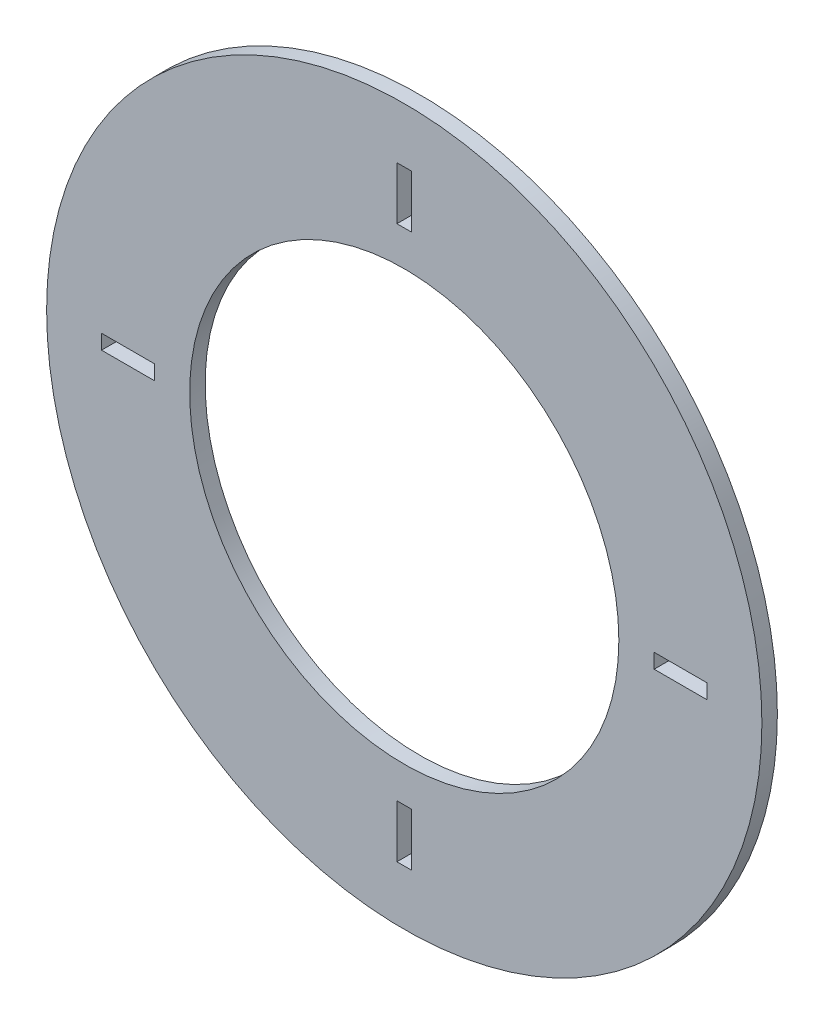
SolidWorks part; units mm, degrees
ref_plane "Front Plane" through (0, 0, 0) normal (1, 0, 0) x (0, 1, 0)
ref_plane "Top Plane" through (0, 0, 0) normal (0, 0, 1) x (0, 1, 0)
ref_plane "Right Plane" through (0, 0, 0) normal (0, 1, 0) x (-1, 0, 0)
sketch "Sketch1" plane through (0, 0, 0) normal (0, 0, 1) x (0, 1, 0)
  circle A0 centre (0, 0) radius 63.5
  circle A1 centre (0, 0) radius 38.1
  dimension "D1" = 127
  dimension "D2" = 25.4
extrude "Boss-Extrude1" add sketch "Sketch1" along normal blind 2.75
sketch "Sketch2" plane through (0, 0, 2.75) normal (0, 0, 1) x (1, 0, 0)
  line L0 (-63.5, 0) -> (63.5, 0) construction
  line L1 (0, 63.5) -> (0, -63.5) construction
  line L2 (53.7452, -1.3025) -> (44.3652, -1.3025)
  line L3 (-1.3025, 53.7452) -> (1.3025, 53.7452)
  line L4 (-1.3025, 53.7452) -> (-1.3025, 44.3652)
  line L5 (-1.3025, 44.3652) -> (1.3025, 44.3652)
  line L6 (1.3025, 53.7452) -> (1.3025, 44.3652)
  line L7 (-1.3025, 53.7452) -> (1.3025, 44.3652) construction
  line L8 (-1.3025, 44.3652) -> (1.3025, 53.7452) construction
  line L9 (44.3652, 1.3025) -> (44.3652, -1.3025)
  line L10 (53.7452, 1.3025) -> (44.3652, 1.3025)
  line L11 (53.7452, 1.3025) -> (53.7452, -1.3025)
  line L12 (-1.3025, -53.7452) -> (-1.3025, -44.3652)
  line L13 (1.3025, -44.3652) -> (-1.3025, -44.3652)
  line L14 (1.3025, -53.7452) -> (1.3025, -44.3652)
  line L15 (1.3025, -53.7452) -> (-1.3025, -53.7452)
  line L16 (-53.7452, 1.3025) -> (-44.3652, 1.3025)
  line L17 (-44.3652, -1.3025) -> (-44.3652, 1.3025)
  line L18 (-53.7452, -1.3025) -> (-44.3652, -1.3025)
  line L19 (-53.7452, -1.3025) -> (-53.7452, 1.3025)
  circle A0 centre (0, 0) radius 63.5 construction
  circle A1 centre (0, 0) radius 38.1 construction
  circle A2 centre (0, 0) radius 44.3652 construction
  point P7 (0, 49.0552)
  point P14 (0, 38.0152)
  point P28 (0, 0)
  dimension "D1" = 6.35
  dimension "D2" = 2.605
  dimension "D3" = 9.38
  dimension "D4" = 4
extrude "Cut-Extrude1" cut sketch "Sketch2" against normal through all
equation "\"w\" = 3 / 8in"
equation "\"PlateThickness\" = 2.75mm"
equation "\"kerf\"= 0.15mm"
equation "\"clearance\" = 0.005mm"
equation "\"SlotW\"= ( \"w\" ) - \"kerf\" + \"clearance\""
equation "\"D2@Sketch2\"=\"SlotH\""
equation "\"D3@Sketch2\"=\"SlotW\""
equation "\"SlotH\"= \"PlateThickness\" + \"clearance\" - \"kerf\""
equation "\"D1@Boss-Extrude1\"=\"PlateThickness\""
